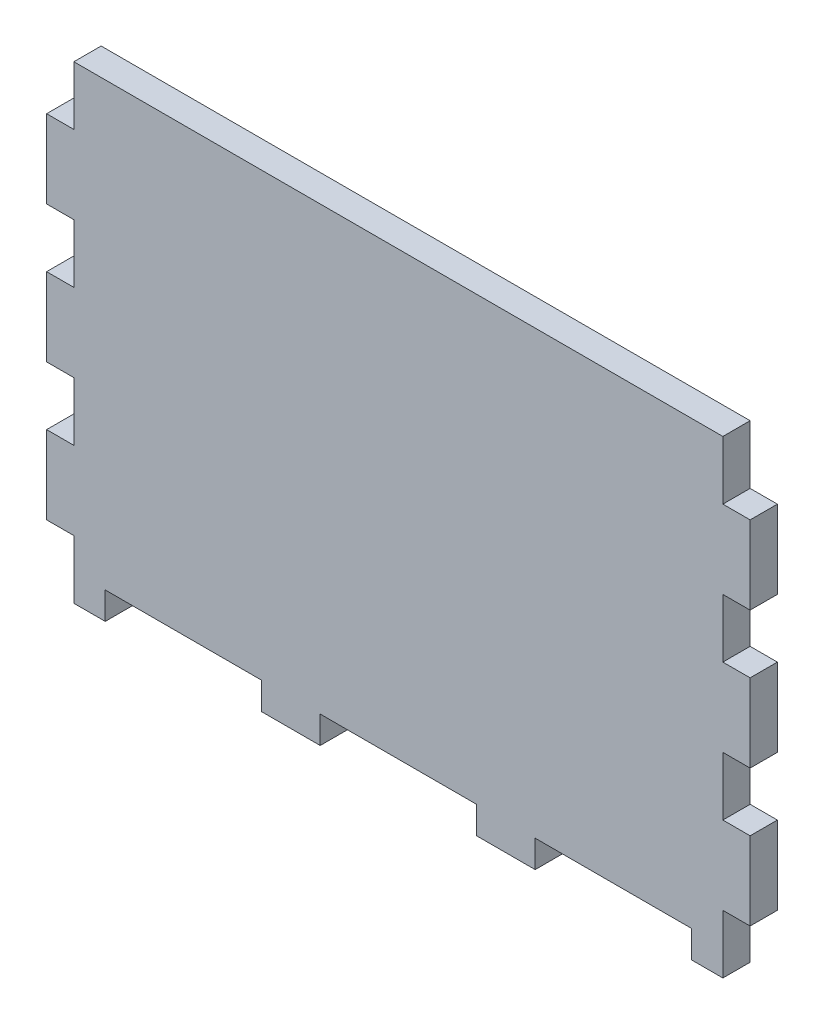
SolidWorks part; units mm, degrees
material "Oak"
ref_plane "Front Plane" through (0, 0, 0) normal (0, 0, 1) x (1, 0, 0)
ref_plane "Top Plane" through (0, 0, 0) normal (0, 1, 0) x (1, 0, 0)
ref_plane "Right Plane" through (0, 0, 0) normal (1, 0, 0) x (0, 0, -1)
sketch "Base_Sketch" plane through (0, 0, 0) normal (0, 0, 1) x (1, 0, 0)
  line L0 (-363.929, 62.4922) -> (-35.509, 62.4922) construction
  line L1 (-352.119, 50.6822) -> (-47.319, 50.6822)
  line L2 (-352.119, 50.6822) -> (-352.119, -140.7078)
  line L3 (-352.119, -140.7078) -> (-47.319, -140.7078)
  line L4 (-47.319, 50.6822) -> (-47.319, -140.7078)
  line L5 (-352.119, 50.6822) -> (-47.319, -140.7078) construction
  line L6 (-352.119, -140.7078) -> (-47.319, 50.6822) construction
  line L7 (-35.509, 62.4922) -> (-35.509, -152.5178) construction
  line L8 (-363.929, -152.5178) -> (-35.509, -152.5178) construction
  line L9 (-363.929, 62.4922) -> (-363.929, -152.5178) construction
  line L10 (-352.119, 50.6822) -> (-47.319, 50.6822) construction
  line L11 (-47.319, 50.6822) -> (-47.319, -152.5178) construction
  dimension "D1" = 11.81
extrude "Boss-Extrude1" add sketch "Base_Sketch" along normal blind 11.81
sketch "Joint_X" plane through (0, 0, 11.81) normal (0, 0, 1) x (1, 0, 0)
  line L1 (-352.119, -152.5178) -> (-326.719, -152.5178)
  line L2 (-352.119, -152.5178) -> (-352.119, -140.7078)
  line L3 (-352.119, -140.7078) -> (-326.719, -140.7078)
  line L4 (-326.719, -152.5178) -> (-326.719, -140.7078)
  point P5 (-326.719, -146.6128)
  dimension "D1" = 11.81
  dimension "D2" = 25.4
sketch "Joint_Y" plane through (0, 0, 11.81) normal (0, 0, 1) x (1, 0, 0)
  line L1 (-352.119, -152.5178) -> (-340.309, -152.5178)
  line L2 (-352.119, -152.5178) -> (-352.119, -127.1178)
  line L3 (-352.119, -127.1178) -> (-340.309, -127.1178)
  line L4 (-340.309, -152.5178) -> (-340.309, -127.1178)
  dimension "D1" = 11.81
  dimension "D2" = 25.4
extrude "Boss-Extrude2" add sketch "Joint_X" against normal blind 11.81
extrude "Cut-Extrude1" cut sketch "Joint_Y" against normal through all
pattern_linear "LPattern1" count 4 spacing 93.1333 along (1, 0, 0) of "Boss-Extrude2"
ref_plane "Plane1" through (-199.719, 0, 0) normal (-1, 0, 0) x (0, 0, 1)
pattern_linear "LPattern2" count 4 spacing 59.2667 along (0, 1, 0) of "Cut-Extrude1"
mirror "Mirror1" about plane through (-199.719, 0, 0) normal (-1, 0, 0) of "Cut-Extrude1", "LPattern2"
equation "\"Material_Thickness\"= \"Material_Thickness@Petrov.Assembly\""
equation "\"D1@Boss-Extrude1\"=\"Material_Thickness\""
equation "\"D1@Joint_X\" = \"Material_Thickness\""
equation "\"D1@Joint_Y\" = \"Material_Thickness\""
equation "\"D1@Boss-Extrude2\"=\"Material_Thickness\""
equation "\"Num_Joints\"= \"Num_Joints@Petrov.Assembly\""
equation "\"D1@LPattern1\"=\"Num_Joints\""
equation "\"D1@Base_Sketch\"=\"Material_Thickness\""
equation "\"D1@LPattern2\"=\"Num_Joints\""
equation "\"Joint_Size\"= \"Joint_Size@Petrov.Assembly\""
equation "\"D2@Joint_Y\"=\"Joint_Size\""
equation "\"D2@Joint_X\"=\"Joint_Size\""
